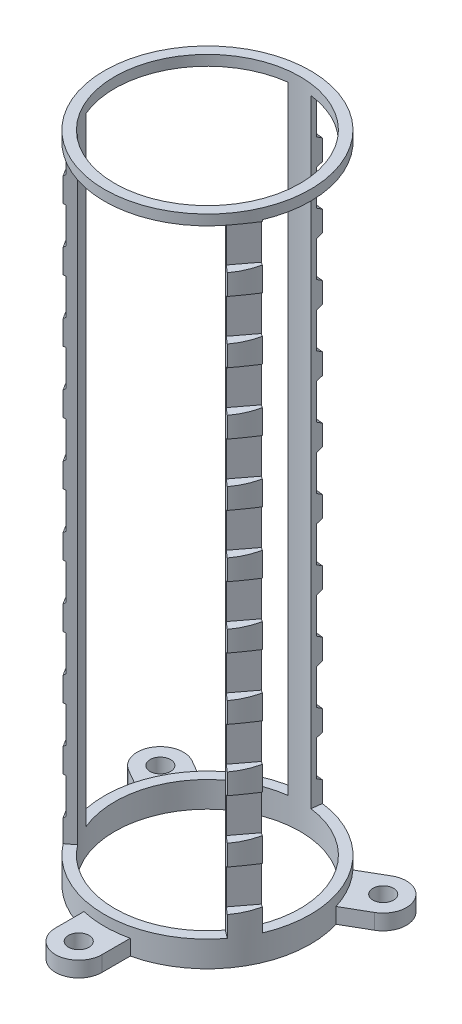
SolidWorks part; units mm, degrees
ref_plane "Front Plane" through (0, 0, 0) normal (0, 0, 1) x (1, 0, 0)
ref_plane "Top Plane" through (0, 0, 0) normal (0, 1, 0) x (1, 0, 0)
ref_plane "Right Plane" through (0, 0, 0) normal (1, 0, 0) x (0, 0, -1)
sketch "Sketch1" plane through (0, 0, 0) normal (0, 1, 0) x (1, 0, 0)
  line L0 (0, 0) -> (0, -25) construction
  line L1 (-4.5, -25) -> (-4.5, -19.4872)
  line L2 (4.5, -25) -> (4.5, -19.4872)
  line L3 (-19.4006, 16.3971) -> (-14.6264, 13.6407)
  line L4 (-23.9006, 8.6029) -> (-19.1264, 5.8465)
  line L5 (23.9006, 8.6029) -> (19.1264, 5.8465)
  line L6 (19.4006, 16.3971) -> (14.6264, 13.6407)
  circle A0 centre (0, 0) radius 20
  circle A1 centre (0, -25) radius 2
  circle A2 centre (0, -25) radius 4.5
  circle A3 centre (0, 0) radius 20
  circle A4 centre (-21.6506, 12.5) radius 4.5
  circle A5 centre (-21.6506, 12.5) radius 2
  circle A6 centre (0, 0) radius 20
  circle A7 centre (21.6506, 12.5) radius 4.5
  circle A8 centre (21.6506, 12.5) radius 2
  circle A9 centre (0, 0) radius 18
  dimension "D1" = 40
  dimension "D2" = 4
  dimension "D3" = 9
  dimension "D6" = 2
  dimension "D4" = 25
  dimension "D5" = 3
extrude "Boss-Extrude1" add sketch "Sketch1" along normal blind 5
sketch "Sketch2" plane through (0, 5, 0) normal (0, 1, 0) x (1, 0, 0)
  circle A0 centre (0, 0) radius 20
  circle A1 centre (0, 0) radius 29.5
extrude "Cut-Extrude1" cut sketch "Sketch2" against normal blind 2
sketch "Sketch3" plane through (0, 5, 0) normal (0, 1, 0) x (1, 0, 0)
  line L0 (0, 0) -> (17.3205, -10) construction
  line L1 (0, 0) -> (23.3827, 13.5) construction
  line L2 (0, 0) -> (18.4327, -7.761)
  line L3 (0, 0) -> (15.9376, -12.0827)
  line L8 (-12.7501, -9.6662) -> (-15.9376, -12.0827) [skipped]
  line L9 (-14.7462, -6.2088) -> (-18.4327, -7.761) [skipped]
  line L10 (0, 0) -> (1.9961, 15.875) [skipped]
  line L11 (0, 0) -> (-1.9961, 15.875) [skipped]
  circle A0 centre (0, 0) radius 20 construction
  circle A1 centre (21.6506, 12.5) radius 2 construction
  arc A2 (15.9376, -12.0827) -> (18.4327, -7.761) centre (0, 0) ccw
  arc A3 (12.7501, -9.6662) -> (14.7462, -6.2088) centre (0, 0) ccw
  arc A4 (12.7501, -9.6662) -> (14.7462, -6.2088) centre (0, 0) ccw
  arc A5 (12.7501, -9.6662) -> (14.7462, -6.2088) centre (0, 0) ccw
  circle M5 centre (0, 0) radius 18
  circle M6 centre (0, 0) radius 20
  dimension "D1" = 60
  dimension "D2" = 2.5
  dimension "D3" = 2.5
  dimension "D4" = 3
extrude "Boss-Extrude2" add sketch "Sketch3" along normal blind 120 contours L3 L2 M5 M6 | A3
sketch "Sketch4" plane through (0, 125, 0) normal (0, 1, 0) x (1, 0, 0)
  circle A0 centre (0, 0) radius 18
  circle A1 centre (0, 0) radius 20
  arc A2 (16.5895, -6.9849) -> (14.3439, -10.8744) centre (0, 0) ccw construction
extrude "Boss-Extrude3" add sketch "Sketch4" along normal blind 2
sketch "Sketch5" plane through (0, 0, 0) normal (-0.6041, 0, 0.7969) x (0.7969, 0, 0.6041)
  line L0 (20, 5) -> (20, 9)
  line L1 (20, 125) -> (20, 5) construction
  line L2 (20, 9) -> (19, 9) construction
  line L3 (19, 9) -> (19, 9.597) construction
  line L4 (20, 9) -> (19, 9.597)
  line L5 (19, 9.597) -> (19, 16.5)
  line L6 (19, 16.5) -> (19, 17) construction
  line L7 (19, 16.5) -> (20, 17)
  line L8 (19, 28.5) -> (20, 29)
  line L9 (19, 21.597) -> (19, 28.5)
  line L10 (20, 17) -> (20, 21)
  line L11 (20, 21) -> (19, 21.597)
  line L12 (19, 40.5) -> (20, 41)
  line L13 (19, 33.597) -> (19, 40.5)
  line L14 (20, 29) -> (20, 33)
  line L15 (20, 33) -> (19, 33.597)
  line L16 (19, 52.5) -> (20, 53)
  line L17 (19, 45.597) -> (19, 52.5)
  line L18 (20, 41) -> (20, 45)
  line L19 (20, 45) -> (19, 45.597)
  line L20 (19, 64.5) -> (20, 65)
  line L21 (19, 57.597) -> (19, 64.5)
  line L22 (20, 53) -> (20, 57)
  line L23 (20, 57) -> (19, 57.597)
  line L24 (19, 76.5) -> (20, 77)
  line L25 (19, 69.597) -> (19, 76.5)
  line L26 (20, 65) -> (20, 69)
  line L27 (20, 69) -> (19, 69.597)
  line L28 (19, 88.5) -> (20, 89)
  line L29 (19, 81.597) -> (19, 88.5)
  line L30 (20, 77) -> (20, 81)
  line L31 (20, 81) -> (19, 81.597)
  line L32 (19, 100.5) -> (20, 101)
  line L33 (19, 93.597) -> (19, 100.5)
  line L34 (20, 89) -> (20, 93)
  line L35 (20, 93) -> (19, 93.597)
  line L36 (19, 112.5) -> (20, 113)
  line L37 (19, 105.597) -> (19, 112.5)
  line L38 (20, 101) -> (20, 105)
  line L39 (20, 105) -> (19, 105.597)
  line L40 (19, 124.5) -> (20, 125)
  line L41 (19, 117.597) -> (19, 124.5)
  line L42 (20, 113) -> (20, 117)
  line L43 (20, 117) -> (19, 117.597)
  line L44 (20, 125) -> (20, 9)
  line M45 (20, 5) -> (20, 125)
  dimension "D1" = 10
extrude "Cut-Extrude2" cut sketch "Sketch5" against normal blind 12 contours L7 L5 L4 M45 | L11 L8 L9 M45 | L15 L12 L13 M45 | L19 L16 L17 M45 | L23 L20 L21 M45 | L27 L24 L25 M45 | L31 L28 L29 M45 | L35 L32 L33 M45 | L39 L36 L37 M45 | L43 L40 L41 M45
pattern_circular "CirPattern1" count 3 over 360 about axis through (0, 0, 0) along (0, 1, 0) of "Boss-Extrude2", "Cut-Extrude2"
